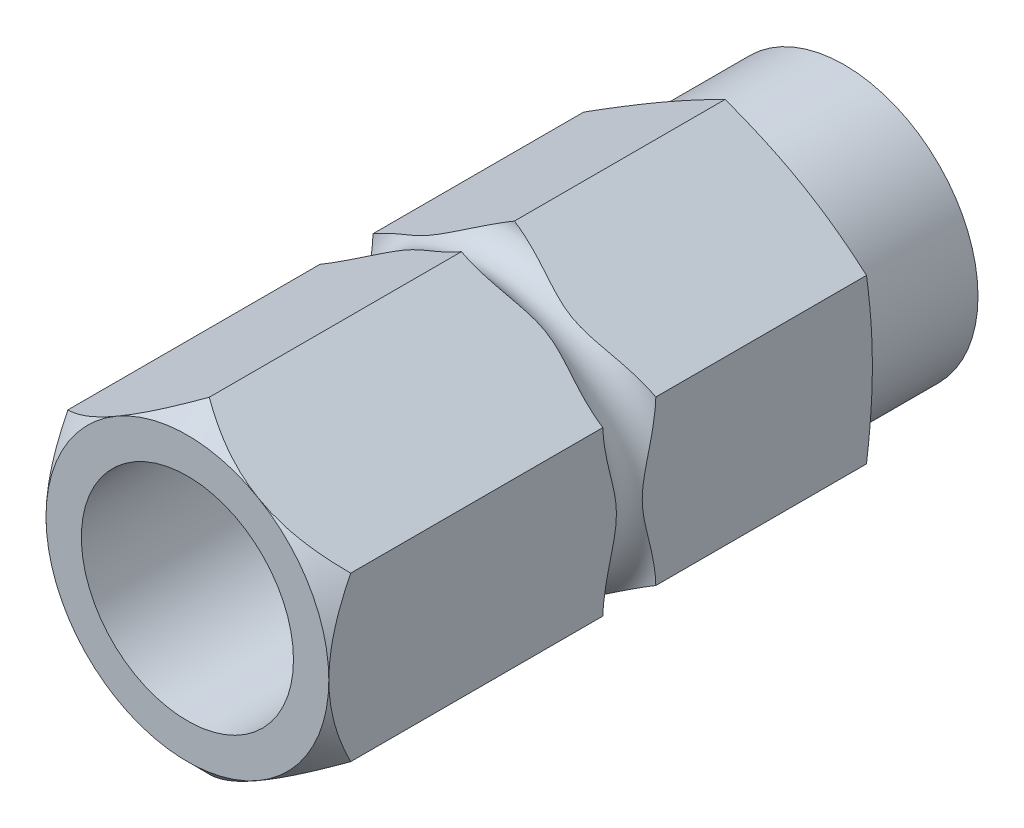
SolidWorks part; units mm, degrees
material "6061-T6 (SS)"
ref_plane "Front Plane" through (0, 0, 0) normal (0, 0, 1) x (1, 0, 0)
ref_plane "Top Plane" through (0, 0, 0) normal (0, 1, 0) x (1, 0, 0)
ref_plane "Right Plane" through (0, 0, 0) normal (1, 0, 0) x (0, 0, -1)
sketch "Sketch1" plane through (0, 0, 0) normal (0, 0, 1) x (1, 0, 0)
  line L1 (-12.7, 7.3323) -> (-12.7, -7.3323)
  line L2 (-12.7, -7.3323) -> (0, -14.6647)
  line L3 (0, -14.6647) -> (12.7, -7.3323)
  line L4 (12.7, -7.3323) -> (12.7, 7.3323)
  line L5 (12.7, 7.3323) -> (0, 14.6647)
  line L6 (0, 14.6647) -> (-12.7, 7.3323)
  circle A0 centre (0, 0) radius 9.525
  circle A1 centre (0, 0) radius 12.7 construction
  dimension "D1" = 19.05
  dimension "D2" = 25.4
extrude "Extrude1" add sketch "Sketch1" against normal blind 59
sketch "Sketch2" plane through (0, 0, 0) normal (1, 0, 0) x (0, 0, -1)
  line L0 (59, 12) -> (49, 12)
  line L1 (49, 12) -> (48.286, 14.6647)
  line L2 (59, 7.3323) -> (59, 14.6647) construction
  line L3 (59, 12) -> (59, 14.6647)
  line L4 (59, 14.6647) -> (0, 14.6647) construction
  line L5 (59, 14.6647) -> (48.286, 14.6647)
  line L6 (0, 7.3323) -> (0, 14.6647) construction
  line L7 (0, 12.7) -> (0, 14.6647)
  line L8 (0, 12.7) -> (1.9647, 14.6647)
  line L9 (1.9647, 14.6647) -> (0, 14.6647)
  line L10 (0, 0) -> (59, 0) construction
  line L11 (59, -7.3323) -> (59, 7.3323) construction
  circle A0 centre (26.9875, 14.7812) radius 2.3813
  dimension "D8" = 4.7625
  dimension "D1" = 12
  dimension "D2" = 105
  dimension "D3" = 10
  dimension "D4" = 12.7
  dimension "D5" = 45
  dimension "D6" = 26.9875
  dimension "D7" = 14.7812
revolve "Cut-Revolve3" cut sketch "Sketch2" angle 360 about L10
